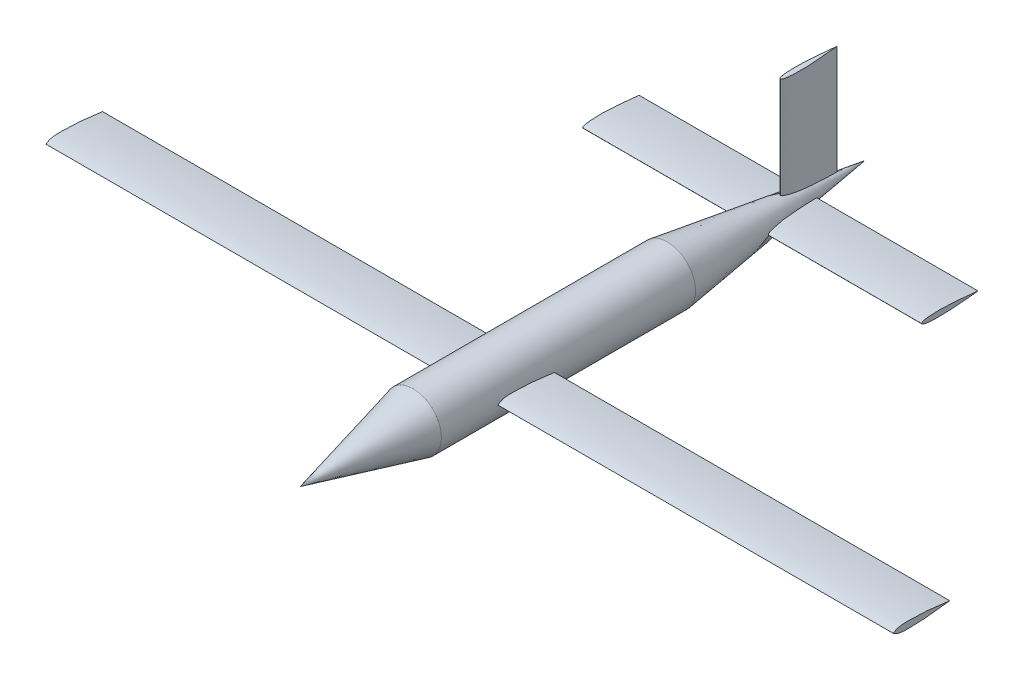
SolidWorks part; units mm, degrees
ref_plane "Front Plane" through (0, 0, 0) normal (0, 0, 1) x (1, 0, 0)
ref_plane "Top Plane" through (0, 0, 0) normal (0, 1, 0) x (1, 0, 0)
ref_plane "Right Plane" through (0, 0, 0) normal (1, 0, 0) x (0, 0, -1)
sketch "Sketch1" plane through (0, 0, 0) normal (1, 0, 0) x (0, 0, -1)
  line L0 (0, 0) -> (50.8, 12.7)
  line L1 (50.8, 12.7) -> (165.1, 12.7)
  line L2 (165.1, 12.7) -> (254, 0)
  line L3 (0, 0) -> (254, 0) construction
  line L4 (0, 0) -> (254, 0)
  dimension "D1" = 12.7
  dimension "D2" = 254
  dimension "D3" = 50.8
  dimension "D4" = 88.9
sketch "Sketch3" plane through (0, 0, 0) normal (1, 0, 0) x (0, 0, -1)
  line L0 (76.2, 0) -> (101.6, 0) construction
  spline S0 degree 3 poles (76.2, 0) (78.0522, 1.4414) (82.4923, 1.5652) (91.0226, 1.3647) (97.3969, 0.5848) (101.6, 0) knots 0 0 0 0 0.257363 0.50401 1 1 1 1
  spline S1 degree 3 poles (76.2, 0) (78.0522, -1.4414) (82.4923, -1.5652) (91.0226, -1.3647) (97.3969, -0.5848) (101.6, 0) knots 0 0 0 0 0.257363 0.50401 1 1 1 1
  point P0 (76.2, 0)
  dimension "D1" = 76.2
  dimension "D2" = 2.54
  dimension "D3" = 6.35
  dimension "D4" = 12.7
  dimension "D5" = 19.05
  dimension "D6" = 25.4
  dimension "D7" = 1.1894
  dimension "D8" = 1.5092
  dimension "D9" = 1.3451
  dimension "D10" = 0.8036
revolve "Revolve1" add sketch "Sketch1" angle 360 about L3
sketch3d "3DSketch1"
  line L0 (0, 0, 0) -> (0, 0, -254) construction
  point P0 (190.5, 0, -63.5105)
  point P1 (76.2, 0, -206.1072)
  point P4 (0, 50.8, -209.5101)
  dimension "D1" = 190.5
  dimension "D2" = 76.2
  dimension "D3" = 50.8
extrude "Extrude1" add sketch "Sketch3" along normal up to vertex (190.5 mm away)
sketch "Sketch4" plane through (0, 0, 0) normal (1, 0, 0) x (0, 0, -1)
  line L0 (0, 0) -> (254, 0) construction
  line L1 (203.2, 0) -> (228.6, 0) construction
  spline S0 degree 3 poles (203.2, 0) (203.4702, 0.4992) (204.7302, 1.0074) (211.5125, 1.4001) (214.2055, 1.2256) (217.2685, 1.0365) (222.4883, 0.6903) (226.5224, 0.2713) (228.6, 0) knots 0 0 0 0 0.16146 0.275608 0.523305 0.574051 0.783072 1 1 1 1
  spline S1 degree 3 poles (203.2, 0) (203.4702, -0.4992) (204.7302, -1.0074) (211.5125, -1.4001) (214.2055, -1.2256) (217.2685, -1.0365) (222.4883, -0.6903) (226.5224, -0.2713) (228.6, 0) knots 0 0 0 0 0.16146 0.275608 0.523305 0.574051 0.783072 1 1 1 1
  dimension "D4" = 12.7
  dimension "D1" = 25.4
  dimension "D2" = 0.9912
  dimension "D3" = 1.1209
  dimension "D5" = 2.54
  dimension "D6" = 203.2
  dimension "D7" = 6.35
  dimension "D8" = 19.05
  dimension "D9" = 1.2576
  dimension "D10" = 0.6696
extrude "Extrude2" add sketch "Sketch4" along normal up to vertex (76.2 mm away)
mirror "Mirror1" about plane through (0, 0, 0) normal (1, 0, 0) of "Extrude1", "Extrude2"
sketch "Sketch5" plane through (0, 0, 0) normal (0, 1, 0) x (1, 0, 0)
  line L0 (0, 215.9) -> (0, 241.3) construction
  spline S0 degree 3 poles (0, 215.9) (0.6742, 216.0299) (0.9213, 217.9174) (1.3636, 221.2501) (1.171, 228.281) (1.0129, 229.4416) (0.6318, 236.2125) (0.4584, 237.0445) (0, 241.3) knots 0 0 0 0 0.195889 0.329618 0.465587 0.508661 0.760362 1 1 1 1
  spline S1 degree 3 poles (0, 215.9) (-0.6742, 216.0299) (-0.9213, 217.9174) (-1.3636, 221.2501) (-1.171, 228.281) (-1.0129, 229.4416) (-0.6318, 236.2125) (-0.4584, 237.0445) (0, 241.3) knots 0 0 0 0 0.195889 0.329618 0.465587 0.508661 0.760362 1 1 1 1
  dimension "D1" = 215.9
  dimension "D2" = 25.4
  dimension "D3" = 0.9912
  dimension "D4" = 1.1209
  dimension "D5" = 2.54
  dimension "D6" = 12.7
  dimension "D7" = 6.35
  dimension "D8" = 19.05
  dimension "D9" = 1.2576
  dimension "D10" = 0.6696
extrude "Extrude3" add sketch "Sketch5" along normal up to vertex (50.8 mm away)
equation "\"BodyDiameter\"= 1"
equation "\"D1@Sketch1\" = \"BodyDiameter\"/2"
equation "\"BodyLength\"= 10"
equation "\"WingChord\"= 1"
equation "\"WingThickness\"= .12"
equation "\"WingShift\"= 3"
equation "\"HTailChord\"= 1"
equation "\"HTailThickness\"= .1"
equation "\"HTailShift\"= 8"
equation "\"VTailChord\"= 1"
equation "\"VTailThickness\"= .1"
equation "\"VTailLocation\"= 8.5"
equation "\"WingSpan\"= 15"
equation "\"HTailSpan\"= 6"
equation "\"VTailSpan\"= 2"
equation "\"D2@Sketch1\" = \"BodyLength\""
equation "\"D3@Sketch1\" = .2*\"BodyLength\""
equation "\"D4@Sketch1\" = .35*\"BodyLength\""
equation "\"D1@Sketch3\" = \"WingShift\""
equation "\"D2@Sketch3\" = \"WingChord\"*.1"
equation "\"D3@Sketch3\" = \"WingChord\"*.25"
equation "\"D4@Sketch3\" = \"WingChord\"*.5"
equation "\"D5@Sketch3\" = .75*\"WingChord\""
equation "\"D1@3DSketch1\" = \"WingSpan\"/2"
equation "\"D2@3DSketch1\" = \"HTailSpan\"/2"
equation "\"D3@3DSketch1\" = \"VTailSpan\""
equation "\"D1@Sketch4\" = \"HTailChord\""
equation "\"D2@Sketch4\"  = \"HTailThickness\" / .2 * \"HTailChord\" * ( .2969 * sqr( .1 ) - .1260 * (  .1 ) - .3515 * (  .1 ) ^ 2 + .2843 * (  .1 ) ^ 3 - .1015 * (  .1 ) ^ 4 )"
equation "\"D3@Sketch4\" = \"HTailThickness\" / .2 * \"HTailChord\" * ( .2969 * sqr( .5 ) - .1260 * (  .5 ) - .3515 * (  .5 ) ^ 2 + .2843 * (  .5 ) ^ 3 - .1015 * (  .5 ) ^ 4 )"
equation "\"D4@Sketch4\" = .5*\"HTailChord\""
equation "\"D5@Sketch4\" = .1*\"HTailChord\""
equation "\"D6@Sketch4\" = \"HTailShift\""
equation "\"D6@Sketch3\" = \"WingChord\""
equation "\"D1@Sketch5\" = \"VTailShift\""
equation "\"D2@Sketch5\" = \"VTailChord\""
equation "\"D3@Sketch5\" = \"VTailThickness\" / .2 * \"VTailChord\" * ( .2969 * sqr( .1 ) - .1260 * (  .1 ) - .3515 * (  .1 ) ^ 2 + .2843 * (  .1 ) ^ 3 - .1015 * (  .1 ) ^ 4 )"
equation "\"D4@Sketch5\" = \"VTailThickness\" / .2 * \"VTailChord\" * ( .2969 * sqr( .5 ) - .1260 * (  .5 ) - .3515 * (  .5 ) ^ 2 + .2843 * (  .5 ) ^ 3 - .1015 * (  .5 ) ^ 4 )"
equation "\"D5@Sketch5\" = .1*\"VTailChord\""
equation "\"D6@Sketch5\" = .5*\"VTailChord\""
equation "\"D7@Sketch3\" = \"WingThickness\" / .2 * \"WingChord\" * ( .2969 * sqr( .1 ) - .1260 * ( .1 ) - .3515 * ( .1 ) ^ 2 + .2843 * ( .1 ) ^ 3 - .1015 * ( .1 ) ^ 4 )"
equation "\"D8@Sketch3\" = \"WingThickness\" / .2 * \"WingChord\" * ( .2969 * sqr( .25 ) - .1260 * (  .25 ) - .3515 * (  .25 ) ^ 2 + .2843 * (  .25 ) ^ 3 - .1015 * (  .25 ) ^ 4 )"
equation "\"D9@Sketch3\" = \"WingThickness\" / .2 * \"WingChord\" * ( .2969 * sqr( .5 ) - .1260 * (  .5 ) - .3515 * (  .5 ) ^ 2 + .2843 * (  .5 ) ^ 3 - .1015 * (  .5 ) ^ 4 )"
equation "\"D10@Sketch3\" = \"WingThickness\" / .2 * \"WingChord\" * ( .2969 * sqr( .75 ) - .1260 * (  .75 ) - .3515 * (  .75 ) ^ 2 + .2843 * (  .75 ) ^ 3 - .1015 * (  .75 ) ^ 4 )"
equation "\"D7@Sketch4\" = .25*\"HTailChord\""
equation "\"D8@Sketch4\" = .75*\"HTailChord\""
equation "\"D9@Sketch4\"  = \"HTailThickness\" / .2 * \"HTailChord\" * ( .2969 * sqr( .25 ) - .1260 * (  .25 ) - .3515 * (  .25 ) ^ 2 + .2843 * (  .25 ) ^ 3 - .1015 * (  .25 ) ^ 4 )"
equation "\"D10@Sketch4\" = \"HTailThickness\" / .2 * \"HTailChord\" * ( .2969 * sqr( .75 ) - .1260 * (  .75 ) - .3515 * (  .75 ) ^ 2 + .2843 * (  .75 ) ^ 3 - .1015 * ( .75 ) ^ 4 )"
equation "\"D7@Sketch5\" = .25*\"VTailChord\""
equation "\"D8@Sketch5\" = .75*\"VTailChord\""
equation "\"D9@Sketch5\" = \"VTailThickness\" / .2 * \"VTailChord\" * ( .2969 * sqr( .25 ) - .1260 * (  .25 ) - .3515 * (  .25 ) ^ 2 + .2843 * (  .25 ) ^ 3 - .1015 * (  .25 ) ^ 4 )"
equation "\"D10@Sketch5\" = \"VTailThickness\" / .2 * \"VTailChord\" * ( .2969 * sqr( .75 ) - .1260 * (  .75 ) - .3515 * (  .75 ) ^ 2 + .2843 * (  .75 ) ^ 3 - .1015 * (  .75 ) ^ 4 )"
